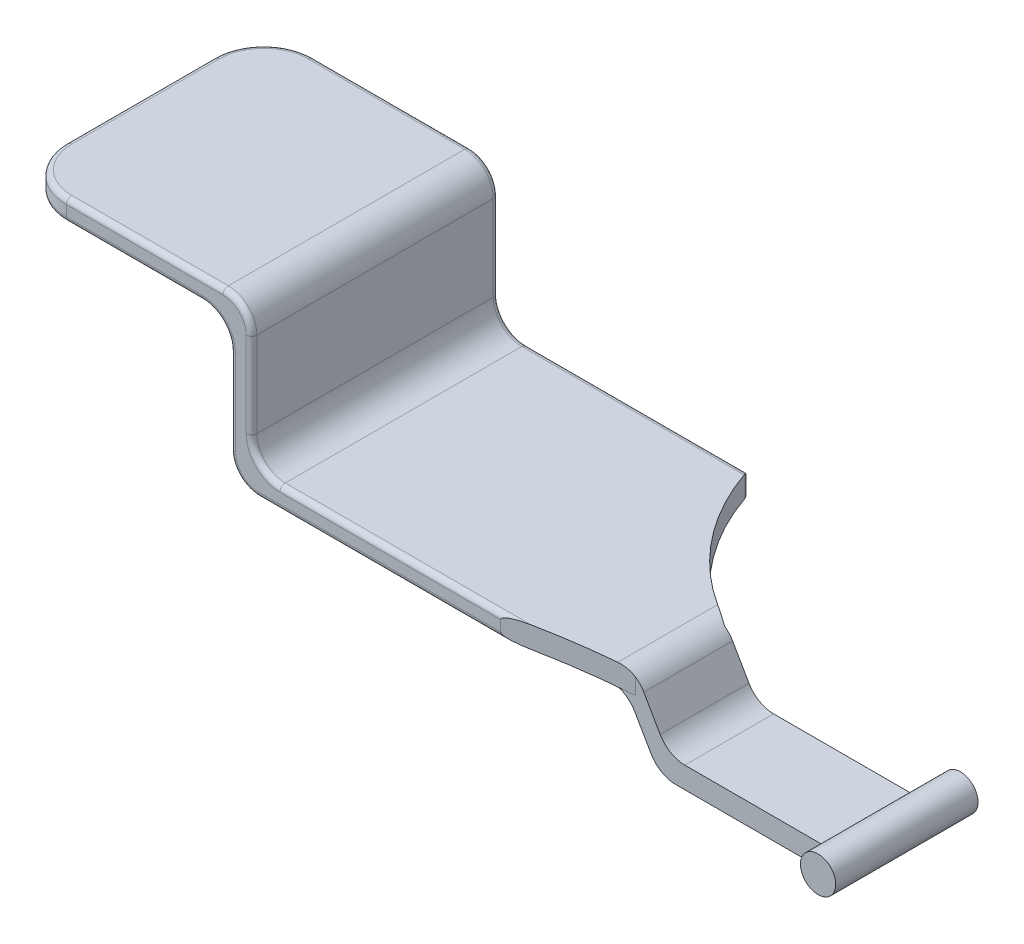
SolidWorks part; units mm, degrees
ref_plane "Front Plane" through (0, 0, 0) normal (0, 0, 1) x (1, 0, 0)
ref_plane "Top Plane" through (0, 0, 0) normal (0, 1, 0) x (1, 0, 0)
ref_plane "Right Plane" through (0, 0, 0) normal (1, 0, 0) x (0, 0, -1)
sketch "Sketch2" plane through (0, 0, 0) normal (0, 0, 1) x (1, 0, 0)
  circle A0 centre (0, 0) radius 2.48
extrude "Boss-Extrude1" add sketch "Sketch2" along normal blind 20
sketch "Sketch3" plane through (0, 0, 0) normal (0, 1, 0) x (1, 0, 0)
  line L1 (0, -5.1) -> (24.73, -5.1)
  line L2 (0, -5.1) -> (0, -17.58)
  line L3 (0, -17.58) -> (24.73, -17.58)
  line L4 (24.73, -5.1) -> (24.73, -17.58)
  dimension "D1" = 12.48
  dimension "D2" = 24.73
extrude "Boss-Extrude3" add sketch "Sketch3" along normal mid plane 3
ref_plane "Plane2" through (0, 0, 5.1) normal (0, 0, 1) x (1, 0, 0)
sketch "Sketch7" plane through (0, 0, 5.1) normal (0, 0, 1) x (1, 0, 0)
  line L0 (21.73, -1.5) -> (24.73, -1.5)
  line L1 (21.73, -1.5) -> (28.062, 9.5)
  line L2 (24.73, -1.5) -> (31.062, 9.5)
  line L3 (28.062, 9.5) -> (31.062, 9.5)
  line L4 (1.9749, -1.5) -> (24.73, -1.5) construction
  dimension "D1" = 11
  dimension "D2" = 3
  dimension "D3" = 2.6
extrude "Boss-Extrude7" add sketch "Sketch7" along normal blind 12.48
ref_plane "Plane3" through (0, 9.5, 0) normal (0, 1, 0) x (1, 0, 0)
sketch "Sketch8" plane through (0, 9.5, 0) normal (0, 1, 0) x (1, 0, 0)
  line L8 (17.5072, -11.34) -> (77.8935, -11.34) construction
  line L9 (72.552, -20.06) -> (44.552, -20.06)
  line L10 (72.552, 14.65) -> (44.552, 14.65)
  line L11 (72.552, -20.06) -> (72.552, 14.65)
  line L12 (28.062, -5.1) -> (28.062, -17.58)
  arc A2 (44.552, -20.06) -> (28.062, -17.58) centre (20.7967, -121.951) ccw
  arc A3 (28.062, -5.1) -> (44.552, 14.65) centre (11.7781, 25.2551) ccw
  dimension "D5" = 12.48
extrude "Boss-Extrude9" add sketch "Sketch8" against normal blind 3
ref_plane "Plane4" through (0, 0, 20.06) normal (0, 0, 1) x (1, 0, 0)
sketch "Sketch9" plane through (0, 0, 20.06) normal (0, 0, 1) x (1, 0, 0)
  line L1 (72.552, 9.5) -> (82.552, 9.5)
  line L2 (72.552, 9.5) -> (72.552, 6.5)
  line L3 (72.552, 6.5) -> (82.552, 6.5)
  line L4 (82.552, 9.5) -> (82.552, 6.5)
  dimension "D1" = 3
  dimension "D2" = 10
extrude "Boss-Extrude10" add sketch "Sketch9" against normal blind 34.71
sketch "Sketch10" plane through (0, 0, 20.06) normal (0, 0, 1) x (1, 0, 0)
  line L1 (82.552, 6.5) -> (79.552, 6.5)
  line L2 (82.552, 6.5) -> (82.552, 29.5)
  line L3 (82.552, 29.5) -> (79.552, 29.5)
  line L4 (79.552, 6.5) -> (79.552, 29.5)
  dimension "D1" = 3
  dimension "D2" = 23
extrude "Boss-Extrude11" add sketch "Sketch10" against normal blind 34.71
sketch "Sketch11" plane through (82.552, 0, 0) normal (1, 0, 0) x (0, 0, -1)
  line L0 (14.65, 6.5) -> (14.65, 29.5) construction
  line L1 (-20.06, 29.5) -> (14.65, 29.5)
  line L2 (-20.06, 29.5) -> (-20.06, 26.5)
  line L3 (-20.06, 26.5) -> (14.65, 26.5)
  line L4 (14.65, 29.5) -> (14.65, 26.5)
  dimension "D1" = 3
extrude "Boss-Extrude12" add sketch "Sketch11" along normal blind 30
fillet "Fillet1" radius 4 8 edges at (28.062, 9.5, 11.34) (23.4569, 1.5, 11.34) (24.73, -1.5, 11.34) (29.3351, 6.5, 11.34) (82.552, 6.5, 2.705) (79.552, 9.5, 2.705) (79.552, 29.5, 2.705) (82.552, 26.5, 2.705)
fillet "Fillet3" radius 7 2 edges at (112.552, 28, 20.06) (112.552, 28, -14.65)
fillet "Fillet4" radius 0.75 27 edges at (61.552, 6.5, 20.06) (81.3805, 7.6716, 20.06) (82.552, 16.5, 20.06) (82.552, 16.5, -14.65) (83.7236, 25.3284, 20.06) (96.052, 26.5, 20.06) (110.5018, 26.5, 18.0097) (112.552, 26.5, 2.705) (110.5018, 26.5, -12.5997) (60.052, 9.5, 20.06) (78.3805, 10.6716, 20.06) (79.552, 19.5, -14.65) (79.552, 19.5, 20.06) (80.7236, 28.3284, 20.06) (94.552, 29.5, 20.06) (110.5018, 29.5, 18.0097) (112.552, 29.5, 2.705) (110.5018, 29.5, -12.5997) (80.7236, 28.3284, -14.65) (78.3805, 10.6716, -14.65) (60.052, 9.5, -14.65) (44.552, 8, -14.65) (61.552, 6.5, -14.65) (81.3805, 7.6716, -14.65) (83.7236, 25.3284, -14.65) (96.052, 26.5, -14.65) (94.552, 29.5, -14.65)
ref_plane "Plane5" through (119.8511, 0, 0) normal (1, 0, 0) x (0, 0, -1)
mirror "Mirror5" about plane through (119.8511, 0, 0) normal (1, 0, 0) of bodies 112
delete or keep bodies "Body-Delete/Keep 1" type delete bodies bodies 112
